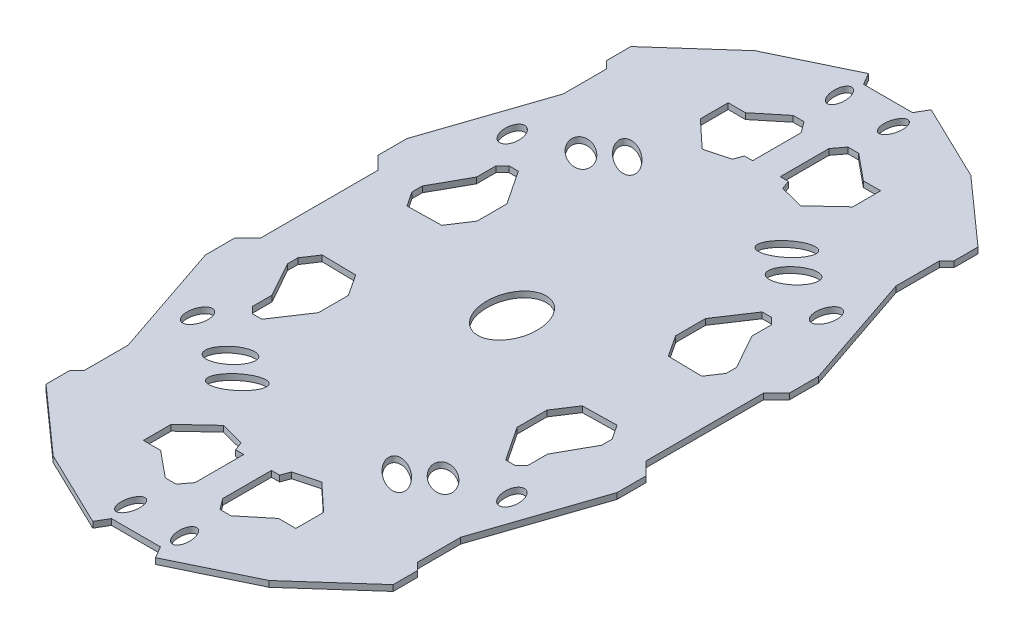
SolidWorks part; units mm, degrees
ref_plane "Front Plane" through (0, 0, 0) normal (0, 0, 1) x (1, 0, 0)
ref_plane "Top Plane" through (0, 0, 0) normal (0, 1, 0) x (1, 0, 0)
ref_plane "Right Plane" through (0, 0, 0) normal (1, 0, 0) x (0, 0, -1)
sketch "Sketch1" plane through (0, 0, 0) normal (0, 1, 0) x (1, 0, 0)
  line L0 (0, 0) -> (640, 0) construction
  line L1 (0, 0) -> (591.2829, 244.9174)
  line L2 (0, 0) -> (591.2829, -244.9174)
  line L3 (0, 0) -> (244.9174, -591.2829)
  line L4 (0, 0) -> (-244.9174, -591.2829)
  line L5 (0, 0) -> (-591.2829, -244.9174)
  line L6 (0, 0) -> (-591.2829, 244.9174)
  line L7 (0, 0) -> (-244.9174, 591.2829)
  line L8 (0, 0) -> (244.9174, 591.2829)
  line L9 (0, 145) -> (55, 145) construction
  line L10 (0, 0) -> (100, 0) construction
  line L11 (0, 0) -> (0, 145) construction
  line L14 (100, 0) -> (100, 145) construction
  circle A0 centre (0, 0) radius 640 construction
  point P15 (0, 0)
  dimension "D1" = 1280
  dimension "D2" = 22.5
  dimension "D4" = 145
  dimension "D5" = 100
  dimension "D6" = 55
  dimension "D3" = 8
sketch "Sketch2" plane through (0, 0, 0) normal (0, 1, 0) x (1, 0, 0)
  line L0 (-486.9956, 169.5033) -> (-66.9956, 169.5033) construction
  line L1 (-188.7141, -86.1278) -> (-188.7141, 241.8722) construction
  line L2 (-501.5908, -106.7095) -> (-501.5908, 221.2905) construction
sketch "Sketch3" plane through (0, 0, 0) normal (0, 1, 0) x (1, 0, 0)
  line L0 (0, 0) -> (381.2468, 0) construction
  line L5 (0, 0) -> (0, 199.4415) construction
  line L7 (10.3387, 158.826) -> (13.2646, 163.8)
  line L8 (13.2646, 163.8) -> (45.5782, 148.1991)
  line L11 (73.9273, 81.0338) -> (86.9334, 42.5399)
  line L12 (86.9334, 42.5399) -> (86.9334, 30.3017)
  line L13 (86.9334, 30.3017) -> (81.4615, 24.8298)
  line L15 (45.5782, 148.1991) -> (73.3112, 123.5038)
  line L16 (73.3112, 123.5038) -> (73.3112, 113.3061)
  line L17 (73.3112, 113.3061) -> (70.2535, 110.2484)
  line L18 (10.3387, 158.826) -> (-10.3387, 158.826)
  line L19 (5.8349, 128.0146) -> (5.8349, 107.4452)
  line L22 (5.8349, 107.4452) -> (9.2702, 107.4452)
  line L25 (9.2702, 107.4452) -> (10.663, 103.7163)
  line L26 (10.663, 103.7163) -> (20.7578, 101.0699)
  line L27 (20.7578, 101.0699) -> (32.199, 111.7601)
  line L28 (32.199, 111.7601) -> (32.199, 123.5038)
  line L29 (32.199, 123.5038) -> (24.9078, 123.5038)
  line L30 (24.9078, 123.5038) -> (13.8412, 132.5856)
  line L31 (13.8412, 132.5856) -> (9.2702, 132.5856)
  line L32 (9.2702, 132.5856) -> (5.8349, 128.0146)
  line L33 (41.9414, 39.7891) -> (51.4866, 54.1602)
  line L34 (51.4866, 54.1602) -> (55.4027, 54.1602)
  line L35 (55.4027, 54.1602) -> (58.1637, 51.3993)
  line L36 (58.1637, 51.3993) -> (58.1637, 43.1872)
  line L37 (58.1637, 43.1872) -> (66.3555, 28.462)
  line L38 (66.3555, 28.462) -> (66.3555, 24.0728)
  line L39 (66.3555, 24.0728) -> (62.2596, 17.9061)
  line L40 (62.2596, 17.9061) -> (47.8497, 18.1669)
  line L41 (47.8497, 18.1669) -> (41.9414, 27.1878)
  line L42 (41.9414, 27.1878) -> (41.9414, 39.7891)
  line L43 (-41.9414, 27.1878) -> (-41.9414, 39.7891)
  line L44 (-47.8497, 18.1669) -> (-41.9414, 27.1878)
  line L45 (-62.2596, 17.9061) -> (-47.8497, 18.1669)
  line L46 (-66.3555, 24.0728) -> (-62.2596, 17.9061)
  line L47 (-66.3555, 28.462) -> (-66.3555, 24.0728)
  line L48 (-58.1637, 43.1872) -> (-66.3555, 28.462)
  line L49 (-58.1637, 51.3993) -> (-58.1637, 43.1872)
  line L50 (-55.4027, 54.1602) -> (-58.1637, 51.3993)
  line L51 (-51.4866, 54.1602) -> (-55.4027, 54.1602)
  line L52 (-41.9414, 39.7891) -> (-51.4866, 54.1602)
  line L53 (-9.2702, 132.5856) -> (-5.8349, 128.0146)
  line L54 (-13.8412, 132.5856) -> (-9.2702, 132.5856)
  line L55 (-24.9078, 123.5038) -> (-13.8412, 132.5856)
  line L56 (-32.199, 123.5038) -> (-24.9078, 123.5038)
  line L57 (-32.199, 111.7601) -> (-32.199, 123.5038)
  line L58 (-20.7578, 101.0699) -> (-32.199, 111.7601)
  line L59 (-10.663, 103.7163) -> (-20.7578, 101.0699)
  line L60 (-9.2702, 107.4452) -> (-10.663, 103.7163)
  line L61 (-5.8349, 107.4452) -> (-9.2702, 107.4452)
  line L62 (-5.8349, 128.0146) -> (-5.8349, 107.4452)
  line L63 (73.9273, 81.0338) -> (70.2535, 91.9072)
  line L64 (70.2535, 91.9072) -> (70.2535, 110.2484)
  line L65 (81.4615, 24.8298) -> (81.4615, -24.8298)
  line L81 (86.9334, -30.3017) -> (81.4615, -24.8298)
  line L82 (86.9334, -42.5399) -> (86.9334, -30.3017)
  line L83 (-5.8349, -128.0146) -> (-5.8349, -107.4452)
  line L84 (-5.8349, -107.4452) -> (-9.2702, -107.4452)
  line L85 (-9.2702, -107.4452) -> (-10.663, -103.7163)
  line L86 (-10.663, -103.7163) -> (-20.7578, -101.0699)
  line L87 (-20.7578, -101.0699) -> (-32.199, -111.7601)
  line L88 (-32.199, -111.7601) -> (-32.199, -123.5038)
  line L89 (-32.199, -123.5038) -> (-24.9078, -123.5038)
  line L90 (-24.9078, -123.5038) -> (-13.8412, -132.5856)
  line L91 (-13.8412, -132.5856) -> (-9.2702, -132.5856)
  line L92 (-9.2702, -132.5856) -> (-5.8349, -128.0146)
  line L93 (-41.9414, -39.7891) -> (-51.4866, -54.1602)
  line L94 (-51.4866, -54.1602) -> (-55.4027, -54.1602)
  line L95 (-55.4027, -54.1602) -> (-58.1637, -51.3993)
  line L96 (-58.1637, -51.3993) -> (-58.1637, -43.1872)
  line L97 (-58.1637, -43.1872) -> (-66.3555, -28.462)
  line L98 (-66.3555, -28.462) -> (-66.3555, -24.0728)
  line L99 (-66.3555, -24.0728) -> (-62.2596, -17.9061)
  line L100 (-62.2596, -17.9061) -> (-47.8497, -18.1669)
  line L101 (-47.8497, -18.1669) -> (-41.9414, -27.1878)
  line L102 (-41.9414, -27.1878) -> (-41.9414, -39.7891)
  line L103 (41.9414, -27.1878) -> (41.9414, -39.7891)
  line L104 (47.8497, -18.1669) -> (41.9414, -27.1878)
  line L105 (62.2596, -17.9061) -> (47.8497, -18.1669)
  line L106 (66.3555, -24.0728) -> (62.2596, -17.9061)
  line L107 (66.3555, -28.462) -> (66.3555, -24.0728)
  line L108 (58.1637, -43.1872) -> (66.3555, -28.462)
  line L109 (58.1637, -51.3993) -> (58.1637, -43.1872)
  line L110 (55.4027, -54.1602) -> (58.1637, -51.3993)
  line L111 (51.4866, -54.1602) -> (55.4027, -54.1602)
  line L112 (41.9414, -39.7891) -> (51.4866, -54.1602)
  line L113 (9.2702, -132.5856) -> (5.8349, -128.0146)
  line L114 (13.8412, -132.5856) -> (9.2702, -132.5856)
  line L115 (24.9078, -123.5038) -> (13.8412, -132.5856)
  line L116 (32.199, -123.5038) -> (24.9078, -123.5038)
  line L117 (32.199, -111.7601) -> (32.199, -123.5038)
  line L118 (20.7578, -101.0699) -> (32.199, -111.7601)
  line L119 (10.663, -103.7163) -> (20.7578, -101.0699)
  line L120 (9.2702, -107.4452) -> (10.663, -103.7163)
  line L121 (5.8349, -107.4452) -> (9.2702, -107.4452)
  line L122 (5.8349, -128.0146) -> (5.8349, -107.4452)
  line L123 (73.9273, -81.0338) -> (86.9334, -42.5399)
  line L124 (73.9273, -81.0338) -> (70.2535, -91.9072)
  line L125 (70.2535, -91.9072) -> (70.2535, -110.2484)
  line L134 (73.3112, -113.3061) -> (70.2535, -110.2484)
  line L135 (73.3112, -123.5038) -> (73.3112, -113.3061)
  line L136 (45.5782, -148.1991) -> (73.3112, -123.5038)
  line L137 (13.2646, -163.8) -> (45.5782, -148.1991)
  line L138 (10.3387, -158.826) -> (13.2646, -163.8)
  line L139 (10.3387, -158.826) -> (-10.3387, -158.826)
  line L140 (-10.3387, -158.826) -> (-13.2646, -163.8)
  line L141 (-13.2646, -163.8) -> (-45.5782, -148.1991)
  line L142 (-45.5782, -148.1991) -> (-73.3112, -123.5038)
  line L143 (-73.3112, -123.5038) -> (-73.3112, -113.3061)
  line L144 (-73.3112, -113.3061) -> (-70.2535, -110.2484)
  line L145 (-70.2535, -91.9072) -> (-70.2535, -110.2484)
  line L146 (-73.9273, -81.0338) -> (-70.2535, -91.9072)
  line L147 (-73.9273, -81.0338) -> (-86.9334, -42.5399)
  line L148 (-86.9334, -42.5399) -> (-86.9334, -30.3017)
  line L149 (-86.9334, -30.3017) -> (-81.4615, -24.8298)
  line L150 (-81.4615, 24.8298) -> (-81.4615, -24.8298)
  line L151 (-86.9334, 30.3017) -> (-81.4615, 24.8298)
  line L152 (-86.9334, 42.5399) -> (-86.9334, 30.3017)
  line L153 (-73.9273, 81.0338) -> (-86.9334, 42.5399)
  line L154 (-70.2535, 91.9072) -> (-70.2535, 110.2484)
  line L155 (-73.3112, 113.3061) -> (-70.2535, 110.2484)
  line L156 (-73.3112, 123.5038) -> (-73.3112, 113.3061)
  line L157 (-45.5782, 148.1991) -> (-73.3112, 123.5038)
  line L158 (-13.2646, 163.8) -> (-45.5782, 148.1991)
  line L159 (-10.3387, 158.826) -> (-13.2646, 163.8)
  line L160 (-73.9273, 81.0338) -> (-70.2535, 91.9072)
  ellipse E0 centre (11.3851, 149.6854) end of major axis (12.0553, 155.2702) minor radius 3.0047
  ellipse E1 centre (33.6925, 82.363) end of major axis (41.1096, 88.3895) minor radius 4.3287
  ellipse E2 centre (44.8955, 74.0187) end of major axis (51.4866, 79.374) minor radius 4.6847
  ellipse E3 centre (66.3555, 66.447) end of major axis (67.1471, 72.2416) minor radius 3.5711
  ellipse E4 centre (-66.3555, 66.447) end of major axis (-67.1471, 72.2416) minor radius 3.5711
  ellipse E5 centre (-44.8955, 74.0187) end of major axis (-51.4866, 79.374) minor radius 4.6847
  ellipse E6 centre (-33.6925, 82.363) end of major axis (-41.1096, 88.3895) minor radius 4.3287
  ellipse E7 centre (-11.3851, 149.6854) end of major axis (-12.0553, 155.2702) minor radius 3.0047
  ellipse E8 centre (-11.3851, -149.6854) end of major axis (-12.0553, -155.2702) minor radius 3.0047
  ellipse E9 centre (-33.6925, -82.363) end of major axis (-41.1096, -88.3895) minor radius 4.3287
  ellipse E10 centre (-44.8955, -74.0187) end of major axis (-51.4866, -79.374) minor radius 4.6847
  ellipse E11 centre (-66.3555, -66.447) end of major axis (-67.1471, -72.2416) minor radius 3.5711
  ellipse E12 centre (66.3555, -66.447) end of major axis (67.1471, -72.2416) minor radius 3.5711
  ellipse E13 centre (44.8955, -74.0187) end of major axis (51.4866, -79.374) minor radius 4.6847
  ellipse E14 centre (33.6925, -82.363) end of major axis (41.1096, -88.3895) minor radius 4.3287
  ellipse E15 centre (11.3851, -149.6854) end of major axis (12.0553, -155.2702) minor radius 3.0047
  ellipse E16 centre (0, 0) end of major axis (0, 14.4715) minor radius 10.663
  point P92 (81.4615, 0)
  point P117 (0, 67.4929)
  point P126 (0, 158.826)
  point P175 (0, -158.826)
  point P180 (0, -158.826)
  point P181 (0, -67.4929)
  point P190 (-81.4615, 0)
  point P193 (-13.2646, 0)
  point P234 (13.2646, 0)
  point P237 (81.4615, 0)
  point P240 (0, 158.826)
extrude "Boss-Extrude2" add sketch "Sketch3" along normal blind 2.5
